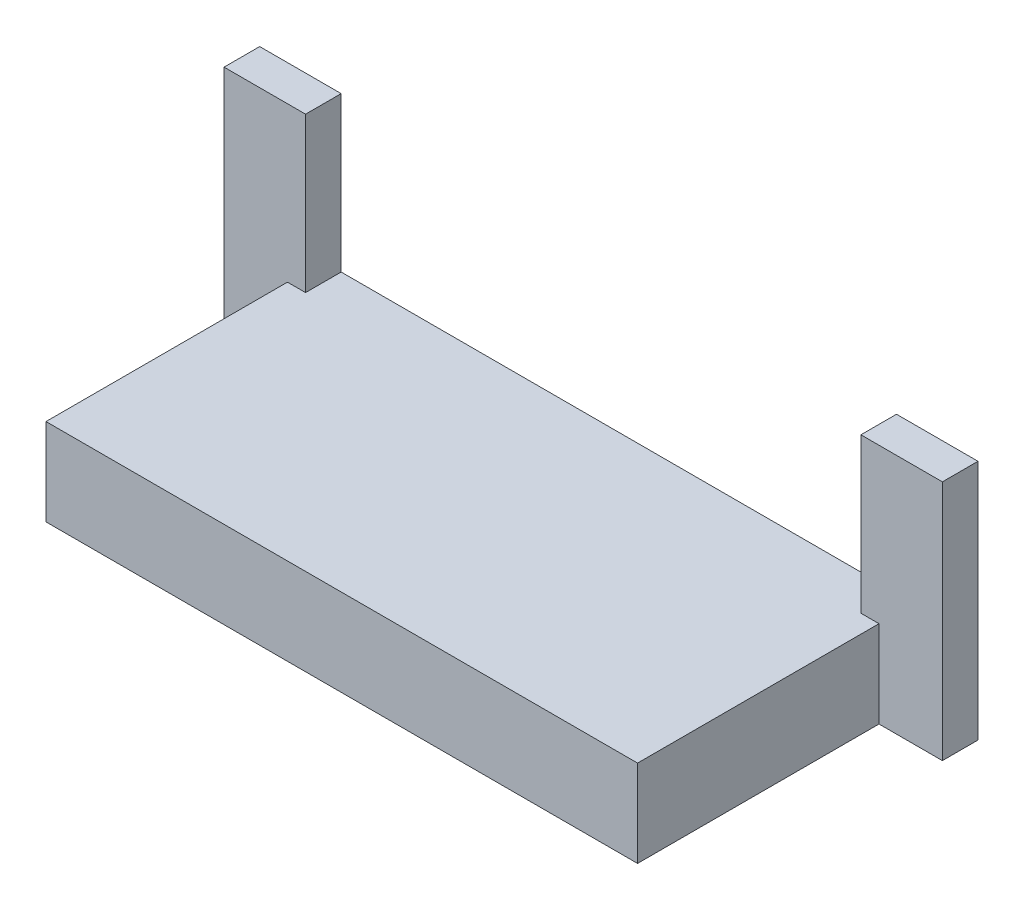
SolidWorks part; units mm, degrees
ref_plane "Front Plane" through (0, 0, 0) normal (0, 0, 1) x (1, 0, 0)
ref_plane "Top Plane" through (0, 0, 0) normal (0, 1, 0) x (1, 0, 0)
ref_plane "Right Plane" through (0, 0, 0) normal (1, 0, 0) x (0, 0, -1)
sketch "Sketch1" plane through (0, 0, 0) normal (0, 0, 1) x (1, 0, 0)
  line L1 (-29.75, 10) -> (-23, 10)
  line L2 (-29.75, 10) -> (-29.75, -10)
  line L3 (-29.75, -10) -> (29.75, -10)
  line L4 (29.75, 10) -> (29.75, -10)
  line L5 (-29.75, 10) -> (29.75, -10) construction
  line L6 (-29.75, -10) -> (29.75, 10) construction
  line L7 (-23, -2.8) -> (23, -2.8)
  line L8 (-23, -2.8) -> (-23, -1.3)
  line L9 (3.8675, -1.3) -> (23, -1.3) construction
  line L10 (23, -2.8) -> (23, -1.3)
  line L11 (-23, 10) -> (-23, -1.3)
  line L12 (23, 10) -> (23, -1.3)
  line L13 (-23, 10) -> (23, 10) construction
  line L14 (23, 10) -> (29.75, 10)
  line L15 (-23, -1.3) -> (-3.8675, -1.3) construction
  line L16 (-3.8675, -1.3) -> (3.8675, -1.3) construction
  point P0 (0, 0)
  point P10 (0, -2.8)
  point P17 (0, 0)
  point P18 (0, 0)
  point P19 (0, 0)
  point P20 (0, 0)
  dimension "D1" = 20
  dimension "D2" = 59.5
  dimension "D3" = 1.5
  dimension "D4" = 46
  dimension "D5" = 12.8
extrude "Boss-Extrude1" add sketch "Sketch1" along normal mid plane 2.95
sketch "Sketch2" plane through (0, 0, 1.475) normal (0, 0, 1) x (1, 0, 0)
  line L0 (23, -2.8) -> (23, 10) construction
  line L1 (-23, -2.8) -> (23, -2.8)
  line L2 (-23, -2.8) -> (-23, -10) construction
  line L3 (-23, -10) -> (23, -10)
  line L4 (23, -2.8) -> (23, -10) construction
  line L5 (-29.75, -10) -> (29.75, -10) construction
  line L6 (-23, -2.8) -> (-24.5, -2.8)
  line L7 (-24.5, -2.8) -> (-24.5, -10)
  line L8 (-24.5, -10) -> (-23, -10)
  line L9 (0, 0) -> (0, -16.6143) construction
  line L10 (24.5, -10) -> (23, -10)
  line L11 (24.5, -2.8) -> (24.5, -10)
  line L12 (23, -2.8) -> (24.5, -2.8)
  dimension "D1" = 1.5
extrude "Boss-Extrude2" add sketch "Sketch2" along normal blind 20
